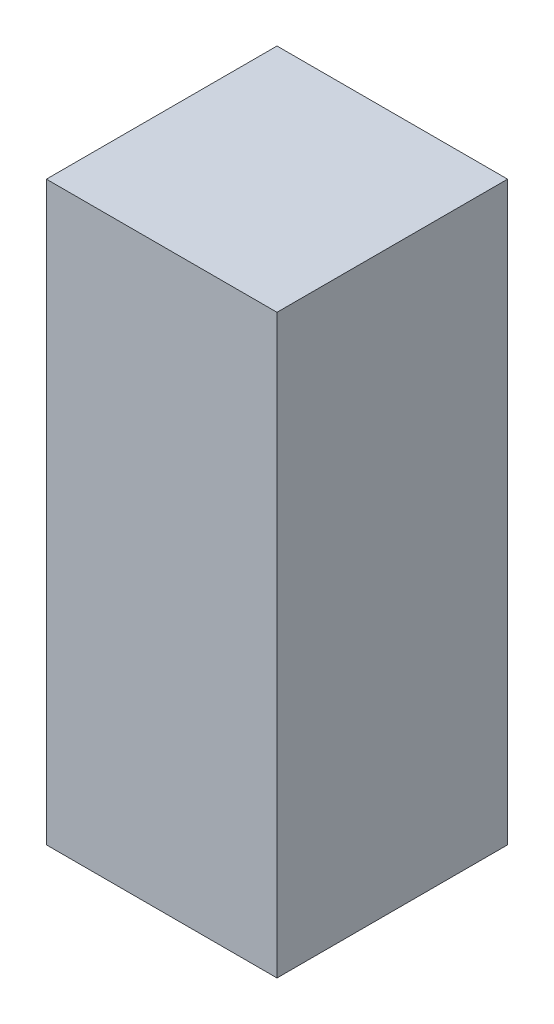
SolidWorks part; units mm, degrees
ref_plane "Front Plane" through (0, 0, 0) normal (0, 0, 1) x (1, 0, 0)
ref_plane "Top Plane" through (0, 0, 0) normal (0, 1, 0) x (1, 0, 0)
ref_plane "Right Plane" through (0, 0, 0) normal (1, 0, 0) x (0, 0, -1)
sketch "Sketch1" plane through (0, 0, 0) normal (0, 1, 0) x (1, 0, 0)
  line L1 (-30.0258, 14.393) -> (20.7742, 14.393)
  line L2 (-30.0258, 14.393) -> (-30.0258, -36.407)
  line L3 (-30.0258, -36.407) -> (20.7742, -36.407)
  line L4 (20.7742, 14.393) -> (20.7742, -36.407)
  dimension "D1" = 50.8
extrude "Boss-Extrude1" add sketch "Sketch1" along normal blind 127
equation "\"TWIST_BLOCK_FACE_SIDE\"=2"
equation "\"TWIST_BLOCK_LENGTH\"=5"
equation "\"D1@Boss-Extrude1\"=\"TWIST_BLOCK_LENGTH\""
equation "\"D1@Sketch1\"=\"TWIST_BLOCK_FACE_SIDE\""
